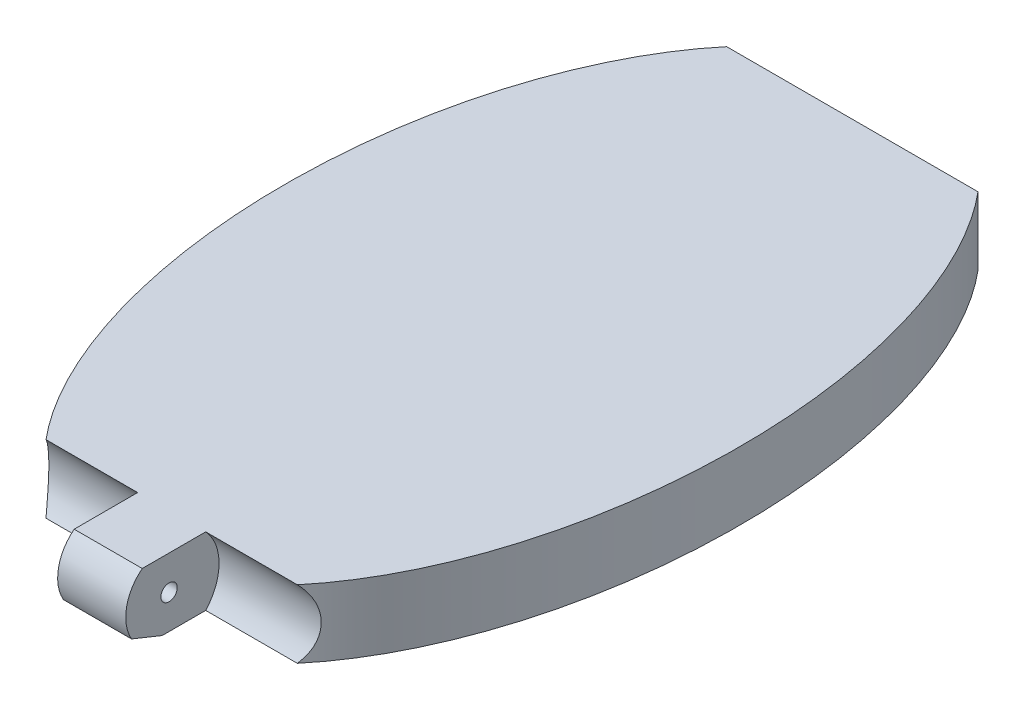
SolidWorks part; units mm, degrees
ref_plane "Front Plane" through (0, 0, 0) normal (0, 0, 1) x (1, 0, 0)
ref_plane "Top Plane" through (0, 0, 0) normal (0, 1, 0) x (1, 0, 0)
ref_plane "Right Plane" through (0, 0, 0) normal (1, 0, 0) x (0, 0, -1)
sketch "Sketch1" plane through (0, 0, 0) normal (0, 1, 0) x (1, 0, 0)
  line L0 (0, 0) -> (0, 58.7756) construction
  line L1 (0, 0) -> (13.1013, 0) construction
  ellipse E0 centre (0, 0) end of major axis (0, 38.1) minor radius 21.209
  dimension "D1" = 42.418
  dimension "D2" = 76.2
extrude "Boss-Extrude1" add sketch "Sketch1" along normal blind 6.35
sketch "Sketch7" plane through (0, 6.35, 0) normal (0, 1, 0) x (1, 0, 0)
  line L0 (-11.7237, 31.75) -> (11.7237, 31.75)
  ellipse E0 centre (0, 0) end of major axis (0, 38.1) minor radius 21.209 construction
  ellipse E1 centre (0, 0) end of major axis (0, 38.1) minor radius 21.209 (11.7237, 31.75) -> (-11.7237, 31.75) ccw
  dimension "D1" = 31.75
extrude "Cut-Extrude6" cut sketch "Sketch7" against normal through all
sketch "Sketch35" plane through (0, 6.35, 0) normal (0, 1, 0) x (1, 0, 0)
  line L0 (0, -11.1645) -> (0, -20.2039) construction
  line L2 (3.175, -38.1) -> (21.209, -38.1)
  line L3 (3.175, -38.1) -> (3.175, -31.75)
  line L4 (3.175, -31.75) -> (21.209, -31.75)
  line L5 (21.209, -38.1) -> (21.209, -31.75)
  line L6 (-3.175, -31.75) -> (-21.209, -31.75)
  line L7 (-3.175, -31.75) -> (-3.175, -38.1)
  line L8 (-3.175, -38.1) -> (-21.209, -38.1)
  line L9 (-21.209, -31.75) -> (-21.209, -38.1)
  ellipse E0 centre (0, 0) end of major axis (0, 38.1) minor radius 21.209 (-11.7237, 31.75) -> (11.7237, 31.75) ccw construction
  dimension "D1" = 6.35
  dimension "D2" = 6.35
extrude "Cut-Extrude17" cut sketch "Sketch35" against normal through all
sketch "Sketch36" plane through (-3.175, 0, 0) normal (-1, 0, 0) x (0, 0, 1)
  line L0 (31.75, 6.35) -> (37.6707, 0) construction
  line L1 (31.75, 3.175) -> (37.6707, 3.175) construction
  line L2 (31.75, 0) -> (31.75, 6.35) construction
  line L3 (37.6707, 6.35) -> (37.6707, 0) construction
  circle A0 centre (35.1675, 3.175) radius 0.762
  point P4 (34.7103, 3.175)
  dimension "D1" = 1.524
  dimension "D2" = 0.4572
extrude "Cut-Extrude18" cut sketch "Sketch36" against normal through all contours A0
sketch "Sketch37" plane through (-3.175, 0, 0) normal (-1, 0, 0) x (0, 0, 1)
  circle A0 centre (35.1675, 3.175) radius 4.6648
extrude "Cut-Extrude19" cut sketch "Sketch37" along normal through all
sketch "Sketch38" plane through (3.175, 0, 0) normal (1, 0, 0) x (0, 0, -1)
  circle A0 centre (-35.1675, 3.175) radius 4.6648
extrude "Cut-Extrude20" cut sketch "Sketch38" along normal through all
sketch "Sketch39" plane through (-3.175, 0, 0) normal (-1, 0, 0) x (0, 0, 1)
  line L1 (37.6707, 6.35) -> (40.0348, 6.35)
  line L2 (37.6707, 6.35) -> (37.6707, 0)
  line L3 (37.6707, 0) -> (40.0348, 0)
  line L4 (40.0348, 6.35) -> (40.0348, 0)
extrude "Cut-Extrude21" cut sketch "Sketch39" against normal through all both and the other way through all
sketch "Sketch40" plane through (-3.175, 0, 0) normal (-1, 0, 0) x (0, 0, 1)
  line L0 (37.6707, 6.35) -> (37.6707, 0)
  arc A0 (37.6707, 0) -> (37.6707, 6.35) centre (35.1675, 3.175) ccw
extrude "Boss-Extrude2" add sketch "Sketch40" against normal up to surface (6.35 mm away) up to face at (3.175, 3.175, 35.9295)
sketch "Sketch41" plane through (0, 0, 0) normal (1, 0, 0) x (0, 0, -1)
  line L0 (-35.1675, 3.175) -> (-35.1675, 0) construction
  line L1 (-37.6707, 0) -> (-31.75, 0) construction
  line L2 (-35.1675, 3.175) -> (-36.4503, 0) construction
  line L3 (-36.4503, 0) -> (-35.1675, 0) construction
  line L4 (-35.8089, 0) -> (-40.5468, 1.9142)
  line L5 (-40.5468, 1.9142) -> (-40.5468, -0.6443)
  line L6 (-40.5468, -0.6443) -> (-35.8089, -0.6443)
  line L7 (-35.8089, -0.6443) -> (-35.8089, 0)
  point P5 (-35.8089, 0)
  dimension "D1" = 22
extrude "Cut-Extrude22" cut sketch "Sketch41" against normal through all both and the other way through all
